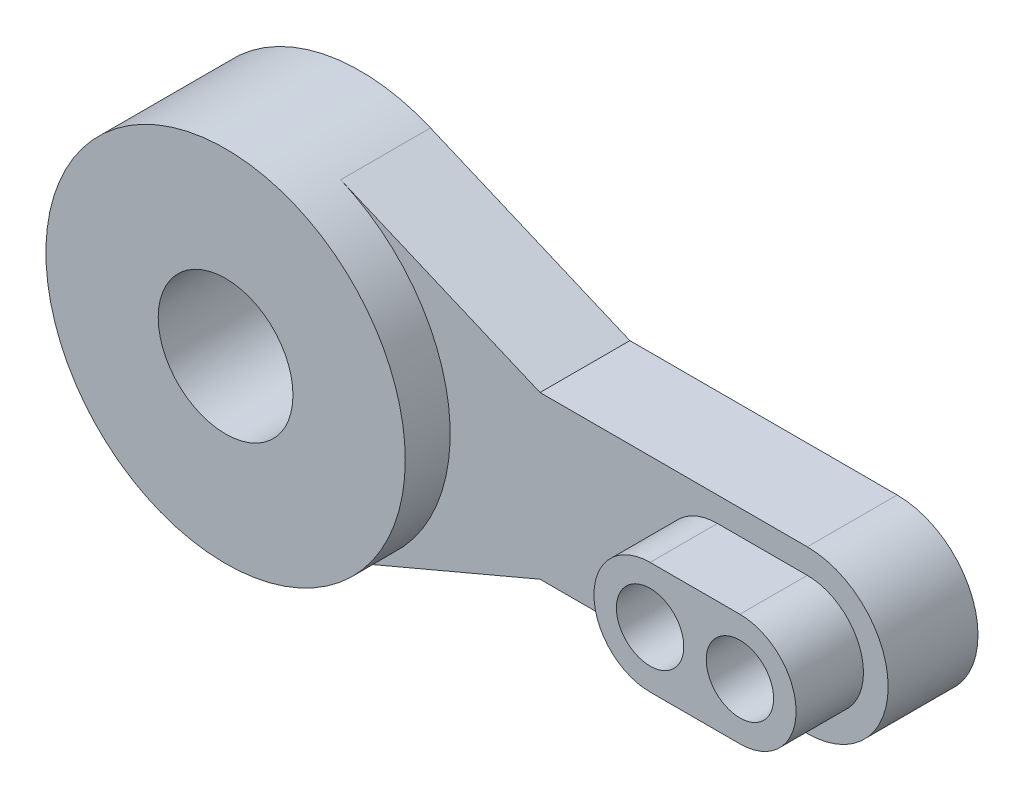
SolidWorks part; units mm, degrees
ref_plane "Top Plane" through (0, 0, 0) normal (0, 0, 1) x (1, 0, 0)
ref_plane "Right Plane" through (0, 0, 0) normal (0, 1, 0) x (1, 0, 0)
ref_plane "Front Plane" through (0, 0, 0) normal (1, 0, 0) x (0, 0, -1)
sketch "Sketch1" plane through (0, 0, 0) normal (0, 0, 1) x (1, 0, 0)
  line L0 (0, 0) -> (23.9, 0) construction
  line L1 (3.1239, 7.3649) -> (12, 3.6)
  line L2 (12, 3.6) -> (23.9, 3.6)
  line L3 (12, -3.6) -> (23.9, -3.6)
  line L4 (3.1239, -7.3649) -> (12, -3.6)
  circle A0 centre (0, 0) radius 3 construction
  circle A1 centre (23.9, 0) radius 1.5 construction
  circle A2 centre (19.9, 0) radius 1.5 construction
  arc A3 (3.1239, 7.3649) -> (3.1239, -7.3649) centre (0, 0) ccw
  arc A4 (23.9, -3.6) -> (23.9, 3.6) centre (23.9, 0) ccw
  point P7 (11.9322, 3.4985)
  point P11 (12.5728, 4)
  point P15 (2.9336, -7.8275)
  point P16 (0, 0)
  point P17 (-8, 0)
  point P18 (27.5, 0)
  dimension "D1" = 23.9
  dimension "D2" = 3
  dimension "D3" = 3
  dimension "D5" = 6
  dimension "D6" = 16
  dimension "D7" = 35.5
  dimension "D4" = 19.9
  dimension "D8" = 12
extrude "Boss-Extrude1" add sketch "Sketch1" along normal blind 4
sketch "Sketch4" plane through (0, 0, 4) normal (0, 0, 1) x (1, 0, 0)
  circle A0 centre (0, 0) radius 8
  arc A1 (3.1239, 7.3649) -> (3.1239, -7.3649) centre (0, 0) ccw construction
extrude "Boss-Extrude2" add sketch "Sketch4" along normal blind 2
sketch "Sketch5" plane through (0, 0, 4) normal (0, 0, 1) x (1, 0, 0)
  line L0 (23.9, 0) -> (19.9, 0) construction
  line L1 (0, 0) -> (23.9, 0) construction
  line L2 (23.9, -2.5) -> (19.9, -2.5)
  line L3 (23.9, 2.5) -> (19.9, 2.5)
  arc A0 (23.9, -2.5) -> (23.9, 2.5) centre (23.9, 0) ccw
  arc A1 (19.9, 2.5) -> (19.9, -2.5) centre (19.9, 0) ccw
  point P5 (21.9, 0)
  point P10 (23.9, 0)
  dimension "D1" = 5
extrude "Boss-Extrude3" add sketch "Sketch5" along normal blind 3
hole_wizard "Ø3.0 (3) Diameter Hole1" positions "Sketch8" profile "Sketch9" hole size "Ø3.0" standard "ISO" end condition through all
sketch "Sketch8" plane through (0, 0, 0) normal (0, 0, -1) x (-1, 0, 0)
  point P0 (-23.9, 0)
  point P3 (-19.9, 0)
sketch "Sketch9" plane through (23.9, 0, 0) normal (1, 0, 0) x (0, 1, 0)
  line L0 (0, 0) -> (0, 7)
  line L1 (0, 7) -> (1.5, 7)
  line L2 (1.5, 7) -> (1.5, 0)
  line L5 (1.5, 0) -> (0, 0)
  line L11 (0, -6.35) -> (0, 107.95) construction
  dimension "Thru Hole Dia." = 3
  dimension "Thru Hole Depth" = 7
hole_wizard "Ø6.0 (6) Diameter Hole1" positions "Sketch10" profile "Sketch11" hole size "Ø6.0" standard "ISO" end condition through all
sketch "Sketch10" plane through (0, 0, 0) normal (0, 0, -1) x (-1, 0, 0)
  point P0 (0, 0)
sketch "Sketch11" plane through (0, 0, 0) normal (1, 0, 0) x (0, 1, 0)
  line L0 (0, 0) -> (0, 7)
  line L1 (0, 7) -> (3, 7)
  line L2 (3, 7) -> (3, 0)
  line L5 (3, 0) -> (0, 0)
  line L11 (0, -6.35) -> (0, 107.95) construction
  dimension "Thru Hole Dia." = 6
  dimension "Thru Hole Depth" = 7
